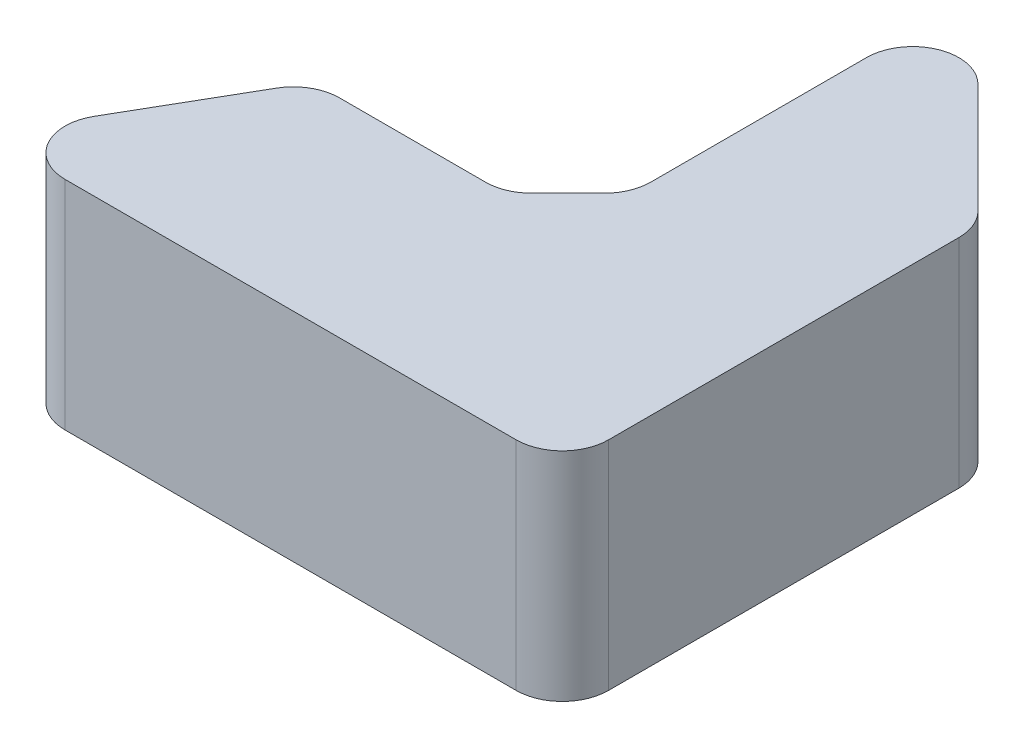
SolidWorks part; units mm, degrees
material "Plain Carbon Steel"
ref_plane "Front Plane" through (0, 0, 0) normal (0, 0, 1) x (1, 0, 0)
ref_plane "Top Plane" through (0, 0, 0) normal (0, 1, 0) x (1, 0, 0)
ref_plane "Right Plane" through (0, 0, 0) normal (1, 0, 0) x (0, 0, -1)
sketch "Sketch1" plane through (0, 0, 0) normal (0, 1, 0) x (1, 0, 0)
  line L0 (0, 0) -> (50, 0)
  line L1 (50, 0) -> (50, 36)
  line L2 (50, 36) -> (32.5, 53.5)
  line L3 (32.5, 53.5) -> (32.5, 23.5)
  line L4 (32.5, 23.5) -> (27, 18)
  line L5 (27, 18) -> (10.3923, 18)
  line L6 (10.3923, 18) -> (0, 0)
  point P3 (32.5, 27.8591)
  point P9 (0, -0.1149)
  dimension "D1" = 17.5
  dimension "D2" = 36
  dimension "D3" = 135
  dimension "D4" = 18
  dimension "D5" = 60
  dimension "D6" = 45
  dimension "D7" = 50
  dimension "D8" = 30
extrude "Boss-Extrude1" add sketch "Sketch1" along normal blind 18.8
fillet "Fillet1" radius 4 7 edges at (50, 9.4, 0) (50, 9.4, -36) (32.5, 9.4, -53.5) (32.5, 9.4, -23.5) (27, 9.4, -18) (10.3923, 9.4, -18) (0, 9.4, 0)
